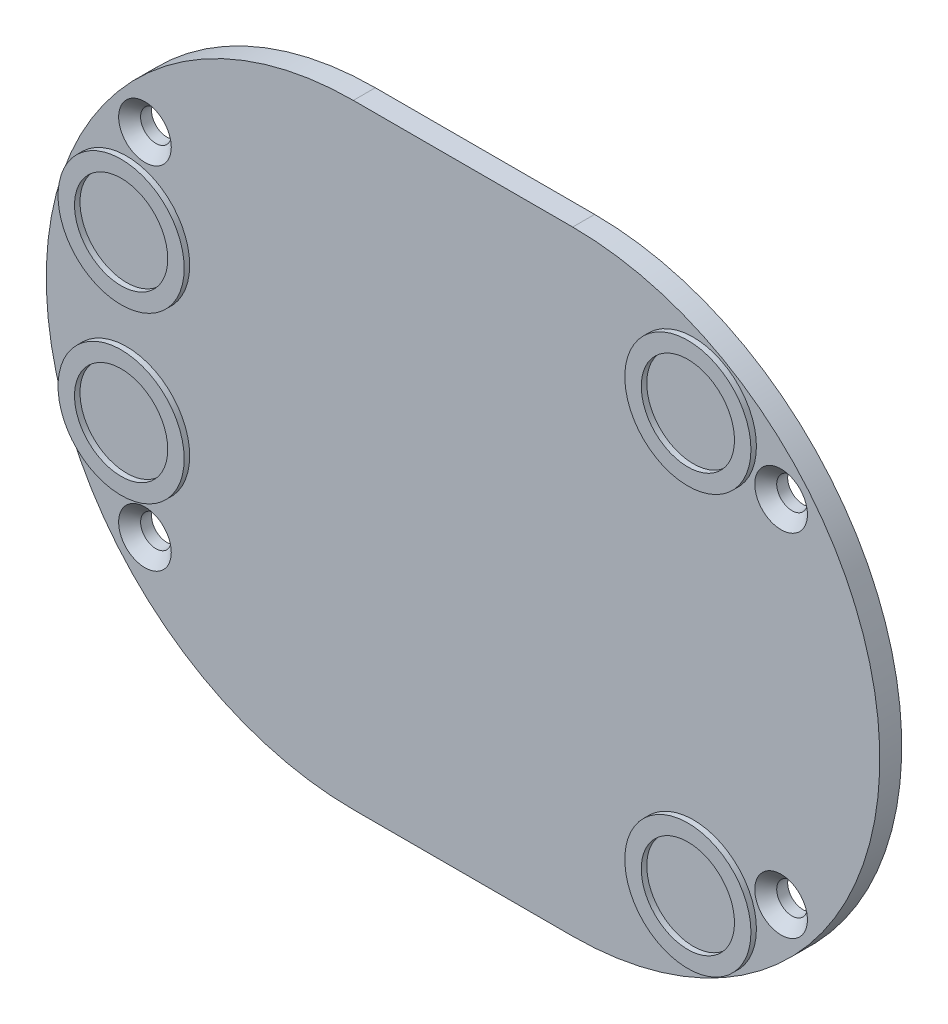
SolidWorks part; units mm, degrees
material "POM 乙缩醛共聚物"
ref_plane "前视基准面" through (0, 0, 0) normal (0, 0, 1) x (1, 0, 0)
ref_plane "上视基准面" through (0, 0, 0) normal (0, 1, 0) x (1, 0, 0)
ref_plane "右视基准面" through (0, 0, 0) normal (1, 0, 0) x (0, 0, -1)
sketch "草图3" plane through (0, 0, 0) normal (0, 0, 1) x (1, 0, 0)
  line L2 (10, -28) -> (-10, -28)
  line L3 (-10, 28) -> (10, 28)
  arc A2 (-10, 28) -> (-10, -28) centre (-10, 0) ccw
  arc A3 (10, -28) -> (10, 28) centre (10, 0) ccw
extrude "凸台-拉伸2" add sketch "草图3" along normal blind 2 contours L3 A3 L2 A2
hole_wizard "打孔尺寸(%根据十字)槽沉头自攻螺钉的类型0" positions "草图5" profile "草图6" countersink size "ST2.2" standard "GB"
sketch "草图5" plane through (0, 0, 2) normal (0, 0, 1) x (1, 0, 0)
  line L1 (12.1906, 0) -> (-13.0853, 0) construction
  line L2 (14.2037, 0) -> (-13.0853, 0) construction
  line L5 (-29, 16) -> (29, 16)
  line L6 (-29, 16) -> (-29, -16)
  line L7 (-29, -16) -> (29, -16)
  line L8 (29, 16) -> (29, -16)
  line L9 (0, -7.6396) -> (0, 21.327) construction
  point P0 (-29, 16)
  point P2 (-29, -16)
  point P4 (29, 16)
  point P6 (29, -16)
  dimension "D1" = 32
  dimension "D2" = 58
sketch "草图6" plane through (-29, 16, 2) normal (1, 0, 0) x (0, -1, 0)
  line L0 (0, 0) -> (0, 10.9412)
  line L1 (0, 10.9412) -> (1.4, 10.1)
  line L2 (1.4, 10.1) -> (1.4, 1)
  line L3 (1.4, 1) -> (2.4, 0)
  line L5 (2.4, 0) -> (0, 0)
  line L6 (-1.4, 1) -> (-2.4, 0) construction
  line L10 (0, 10.9412) -> (-1.4, 10.1) construction
  line L11 (0, -6.35) -> (0, 107.95) construction
  dimension "孔直径" = 2.8
  dimension "孔深度" = 10.1
  dimension "近端锥形沉头孔直径" = 4.8
  dimension "近端锥形沉头孔角度" = 90
  dimension "导头角度" = 118
sketch "草图7" plane through (0, 0, 2) normal (0, 0, 1) x (1, 0, 0)
  circle A0 centre (-30.6732, 7.5244) radius 4.25
  circle A1 centre (-30.6732, -7.5244) radius 4.25
  circle A2 centre (21, -19.0526) radius 4.25
  circle A3 centre (21, 19.0526) radius 4.25
  dimension "D1" = 8.5
extrude "拉伸-薄壁1" add sketch "草图7" along normal blind 0.5 thin
sketch "草图10" plane through (0, 0, 2) normal (0, 0, 1) x (1, 0, 0)
  arc A0 (-24.2149, -8.3777) -> (-8.555, -16.4366) centre (-10, 0) ccw
  dimension "D1" = 16.5
extrude "拉伸-薄壁2" add sketch "草图10" against normal blind 21.5 thin
chamfer "倒角1" distance 1.5 angle 45 2 edges at (-18.6941, -16.8942, 0) (-17.5501, -14.6713, 0)
